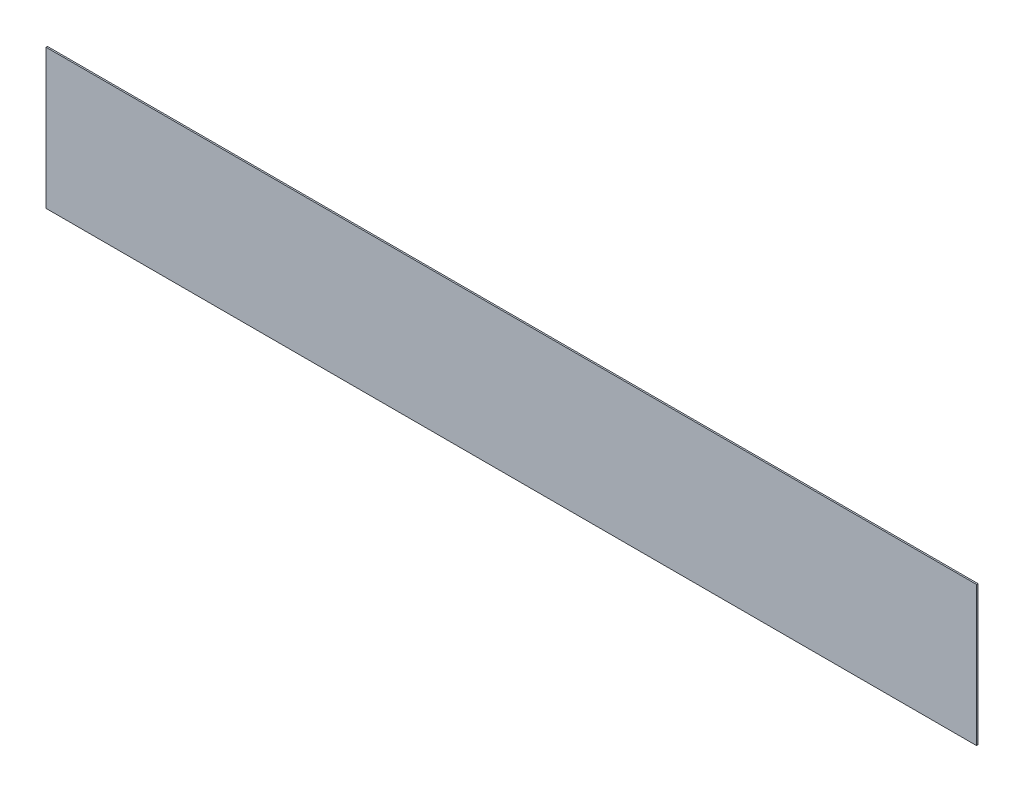
SolidWorks part; units mm, degrees
ref_plane "Front Plane" through (0, 0, 0) normal (0, 0, 1) x (1, 0, 0)
ref_plane "Top Plane" through (0, 0, 0) normal (0, 1, 0) x (1, 0, 0)
ref_plane "Right Plane" through (0, 0, 0) normal (1, 0, 0) x (0, 0, -1)
sketch "Sketch1" plane through (0, 0, 0) normal (0, 0, 1) x (1, 0, 0)
  line L1 (508, -76.2) -> (-508, -76.2)
  line L2 (508, -76.2) -> (508, 76.2)
  line L3 (508, 76.2) -> (-508, 76.2)
  line L4 (-508, -76.2) -> (-508, 76.2)
  line L5 (508, -76.2) -> (-508, 76.2) construction
  line L6 (508, 76.2) -> (-508, -76.2) construction
  point P0 (0, 0)
  dimension "D1" = 152.4
  dimension "D2" = 1016
extrude "Boss-Extrude1" add sketch "Sketch1" along normal blind 1.5875
